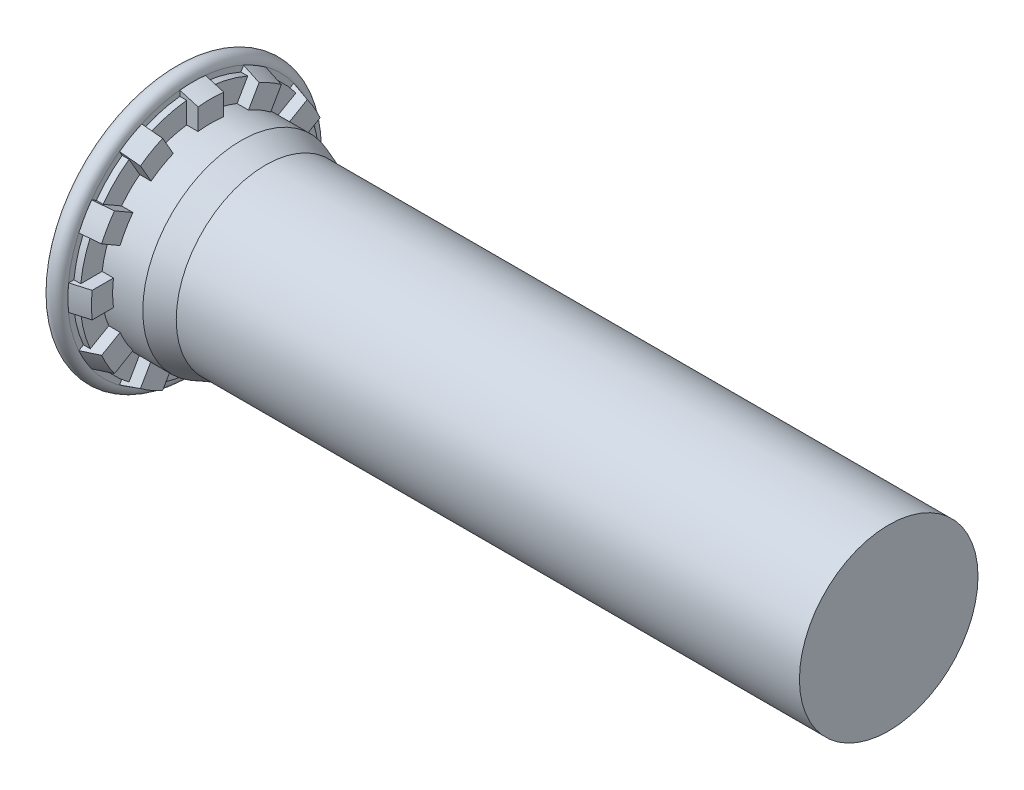
SolidWorks part; units mm, degrees
revolve "BaseBody" add sketch "BodySke" angle 360 about L6
sketch "BodySke" plane through (0, 0, 0) normal (0, 0, 1) x (1, 0, 0)
  line L0 (0, 0) -> (0, 3.4925)
  line L1 (0.51, 3.4975) -> (0.51, 3.4925)
  line L2 (0.51, 3.4925) -> (1.02, 3.3436)
  line L3 (2.55, 2.5) -> (20, 2.5)
  line L4 (20, 2.5) -> (20, 0)
  line L5 (20, 0) -> (0, 0)
  line L6 (0, 0) -> (50.554, 0) construction
  line L7 (1.02, 3.3436) -> (1.02, 2.75)
  line L8 (1.8631, 2.75) -> (1.02, 2.75)
  line L9 (-9.525, 3.75) -> (9.525, 3.75) construction
  line L11 (2.55, 2.5) -> (1.8631, 2.75)
  line L13 (9.525, -3.75) -> (-9.525, -3.75) construction
  line L14 (0.0051, 3.4975) -> (0.0051, 3.4925)
  line L15 (0, 3.4925) -> (0.0051, 3.4925)
  arc A0 (0.0051, 3.4975) -> (0.51, 3.4975) centre (0.2575, 3.4975) cw
  dimension "Length" = 20
  dimension "H_dia" = 7.5
  dimension "Shoulder_lower_dia" = 6.985
  dimension "Shoulder_upper_dia" = 6.6873
  dimension "D1" = 0.0051
  dimension "D2" = 0.0051
  dimension "Shoulder_ht" = 1.02
  dimension "T_dim" = 0.51
  dimension "Diameter" = 5
  dimension "Neck_dia" = 5.5
  dimension "Neck_len" = 2.55
  dimension "D3" = 20
cosmetic thread "ThreadCosmetic" [suppressed] parameters "Thread_length"=15.621, "Thread_minor"=4.8387
extrude "RibCut1" cut sketch "RibCut1Ske" against normal blind 0.3187
sketch "RibCut1Ske" plane through (1.02, 0, 0) normal (1, 0, 0) x (0, 0, -1)
  line L0 (0.3589, 2.7265) -> (0.3589, 3.7328)
  line L1 (1.0524, 2.5407) -> (1.5555, 3.4122)
  line L2 (0, 0) -> (0, 4.9784) construction
  line L3 (0, 0) -> (0.3589, 2.7265) construction
  line L4 (0, 0) -> (1.0524, 2.5407) construction
  arc A1 (1.0524, 2.5407) -> (0.3589, 2.7265) centre (0, 0) ccw
  arc A2 (1.5555, 3.4122) -> (0.3589, 3.7328) centre (0, 0) ccw
  dimension "Angle" = 30
  dimension "Inner_dia" = 5.5
  dimension "Outer_dia" = 7.5
  dimension "Rib_root_half_angle" = 7.5
  dimension "Rib_root_gap_angle" = 15
ref_plane "Plane1" through (0, 0, 0) normal (0, 0, 1) x (1, 0, 0)
ref_plane "Plane2" through (0, 0, 0) normal (0, 1, 0) x (1, 0, 0)
ref_plane "Plane3" through (0, 0, 0) normal (1, 0, 0) x (0, 0, -1)
sketch "RibCut2Ske" plane through (1.02, 0, 0) normal (1, 0, 0) x (0, 0, -1)
  line L0 (0.3589, 3.3243) -> (0.3589, 3.7328)
  line L1 (1.3513, 3.0584) -> (1.5555, 3.4122)
  line L2 (0.3589, 2.7265) -> (0.3589, 4.5382) construction
  line L3 (0, 0) -> (0, 5.0239) construction
  line L4 (0, 0) -> (0.3589, 2.7265) construction
  line L5 (0, 0) -> (1.0524, 2.5407) construction
  line L6 (1.0524, 2.5407) -> (1.9618, 4.1158) construction
  arc A1 (1.3513, 3.0584) -> (0.3589, 3.3243) centre (0, 0) ccw
  arc A2 (1.5555, 3.4122) -> (0.3589, 3.7328) centre (0, 0) ccw
  circle A4 centre (0, 0) radius 2.75 construction
  dimension "Angle" = 30
  dimension "Outer_dia" = 7.5
  dimension "Rib_root_half_angle" = 7.5
  dimension "Rib_root_gap_angle" = 15
extrude "RibCut2" cut sketch "RibCut2Ske" against normal blind 0.51
pattern_circular "RibCutsPat" count 12 every 30 about axis through (0, 0, 0) along (1, 0, 0) of "RibCut2", "RibCut1"
equation "' \"Diameter@BodySke\" = 5"
equation "' \"Length@BodySke\" = 20"
equation "' \"Neck_dia@BodySke\" = 5.5"
equation "' \"H_dia@BodySke\" = 7.5"
equation "' \"Neck_len@BodySke\" = 2.55"
equation "\"T_dim@BodySke\" = \"Neck_len@BodySke\" * 0.2"
equation "\"Shoulder_ht@BodySke\" = \"Neck_len@BodySke\" * 0.4"
equation "\"Shoulder_lower_dia@BodySke\" = \"H_dia@BodySke\" - \"Neck_len@BodySke\" * 0.2 - .005"
equation "\"Shoulder_upper_dia@BodySke\" = ( \"Shoulder_lower_dia@BodySke\" + \"Diameter@BodySke\" ) /2"
equation "\"Shoulder_upper_dia@BodySke\" = \"Diameter@BodySke\" +  ( \"Shoulder_lower_dia@BodySke\" - \"Diameter@BodySke\" ) * 0.85"
equation "\"Num_ribs@RibCutsPat\" = 12"
equation "\"Angle@RibCutsPat\" = 360 / \"Num_ribs@RibCutsPat\""
equation "\"Angle@RibCut1Ske\" =\"Angle@RibCutsPat\""
equation "\"Rib_root_half_angle@RibCut1Ske\" = \"Angle@RibCut1Ske\" / 4"
equation "\"Rib_root_gap_angle@RibCut1Ske\" = \"Angle@RibCut1Ske\" - (2 * \"Rib_root_half_angle@RibCut1Ske\" )"
equation "\"Inner_dia@RibCut1Ske\" = \"Neck_dia@BodySke\""
equation "\"Outer_dia@RibCut1Ske\" = \"H_dia@BodySke\""
equation "\"Depth@RibCut1\" =  \"Neck_len@BodySke\" * 0.125"
equation "\"Angle@RibCut2Ske\" =\"Angle@RibCutsPat\""
equation "\"Rib_root_half_angle@RibCut2Ske\" = \"Angle@RibCut1Ske\" / 4"
equation "\"Rib_root_gap_angle@RibCut2Ske\" = \"Angle@RibCut1Ske\" - (2 * \"Rib_root_half_angle@RibCut1Ske\" )"
equation "\"Rib_root_dia@RibCut2Ske\" = \"Neck_dia@BodySke\""
equation "\"Inner_dia@RibCut2Ske\" = \"Shoulder_upper_dia@BodySke\""
equation "\"Outer_dia@RibCut2Ske\" = \"H_dia@BodySke\""
equation "\"Depth@RibCut2\" =  \"Neck_len@BodySke\" * 0.2"
